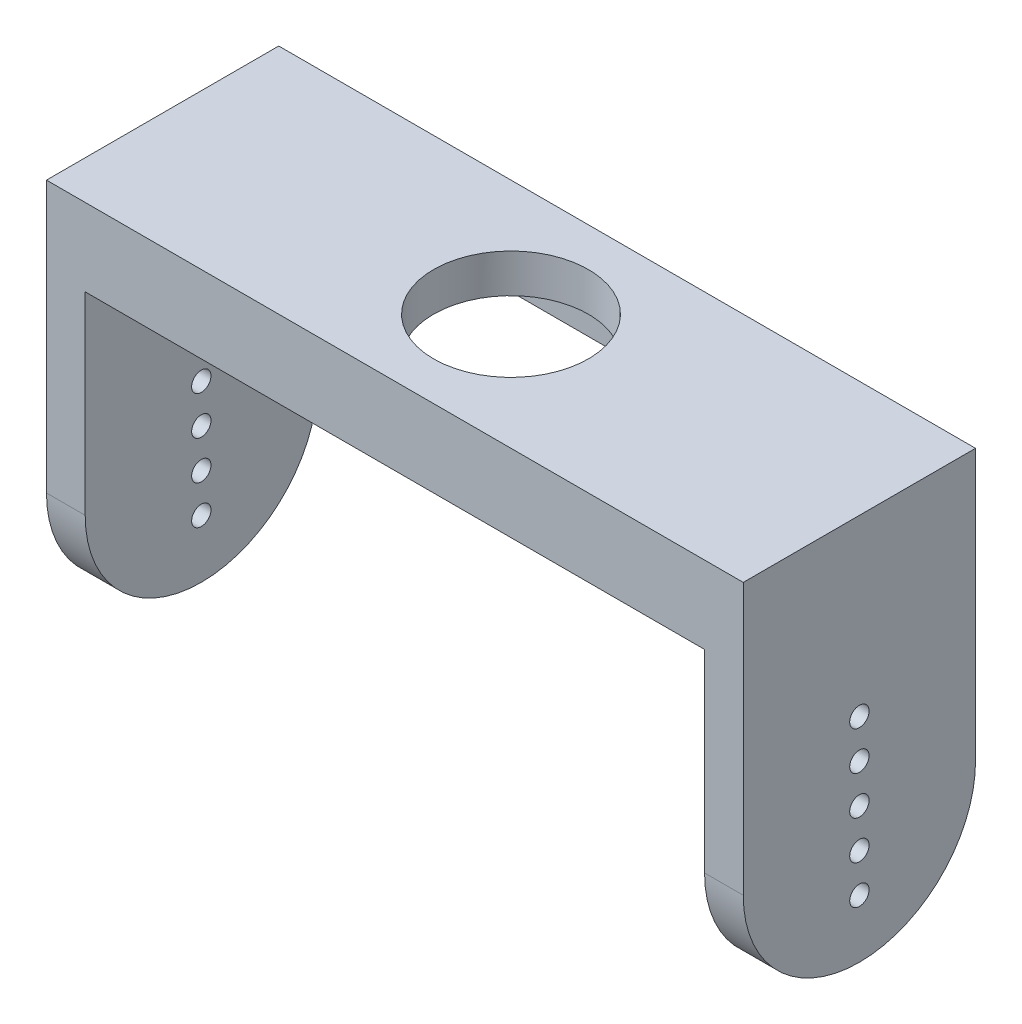
SolidWorks part; units mm, degrees
ref_plane "Front Plane" through (0, 0, 0) normal (0, 0, 1) x (1, 0, 0)
ref_plane "Top Plane" through (0, 0, 0) normal (0, 1, 0) x (1, 0, 0)
ref_plane "Right Plane" through (0, 0, 0) normal (1, 0, 0) x (0, 0, -1)
sketch "Sketch1" plane through (0, 0, 0) normal (0, 0, 1) x (1, 0, 0)
  line L1 (-18, 10) -> (18, 10)
  line L2 (-18, 10) -> (-18, -10)
  line L3 (-18, -10) -> (18, -10)
  line L4 (18, 10) -> (18, -10)
  line L5 (-18, 10) -> (18, -10) construction
  line L6 (-18, -10) -> (18, 10) construction
  point P0 (0, 0)
  dimension "D1" = 20
  dimension "D2" = 36
extrude "Boss-Extrude1" add sketch "Sketch1" along normal blind 12
sketch "Sketch2" plane through (18, 0, 0) normal (1, 0, 0) x (0, 0, -1)
  line L4 (0, -10) -> (0, 10)
  line L5 (0, 10) -> (-12, 10)
  line L6 (-12, 10) -> (-12, -10)
  line L7 (-12, -10) -> (0, -10)
  line L8 (0, -4) -> (0, 10)
  line L9 (0, 10) -> (-12, 10)
  line L10 (-12, 10) -> (-12, -4)
  arc A0 (-12, -4) -> (0, -4) centre (-6, -4) ccw
  line M1 (0, -10) -> (0, 10)
  line M3 (-12, 10) -> (-12, -10)
  line M4 (-12, -10) -> (0, -10)
  dimension "D1" = 0
sketch "Sketch3" plane through (0, 0, 12) normal (0, 0, 1) x (1, 0, 0)
  line L0 (-16, 8) -> (-16, -8)
  line L1 (-16, -8) -> (16, -8)
  line L2 (16, -8) -> (16, 8)
  line L3 (16, 8) -> (-16, 8)
  line L4 (18, -10) -> (18, 10)
  line L5 (18, 10) -> (-18, 10)
  line L6 (-18, 10) -> (-18, -10)
  line L7 (-18, -10) -> (18, -10)
  line L8 (18, -10) -> (18, 10)
  line L9 (18, 10) -> (-18, 10)
  line L10 (-18, 10) -> (-18, -10)
  line L11 (-18, -10) -> (18, -10)
  dimension "D1" = 0
  dimension "D2" = 2
extrude "Cut-Extrude1" cut sketch "Sketch3" against normal blind 12 contours L2 L3 L0 L1
sketch "Sketch4" plane through (0, -8, 0) normal (0, 1, 0) x (1, 0, 0)
  line L0 (16, 0) -> (16, -12) construction
  line L1 (-16, 0) -> (16, 0)
  line L2 (-16, 0) -> (-16, -12)
  line L3 (-16, -12) -> (16, -12)
  line L4 (16, 0) -> (16, -12)
extrude "Cut-Extrude2" cut sketch "Sketch4" against normal blind 12
extrude "Cut-Extrude3" cut sketch "Sketch2" against normal through all contours A0 M3 M4 | A0 M4 M1
sketch "Sketch5" plane through (0, 10, 0) normal (0, 1, 0) x (1, 0, 0)
  line L0 (18, -6) -> (-18, -6) construction
  line L1 (18, -12) -> (18, 0) construction
  line L2 (-18, -12) -> (-18, 0) construction
  circle A0 centre (0, -6) radius 4
  dimension "D1" = 8
extrude "Cut-Extrude4" cut sketch "Sketch5" against normal blind 10 contours A0
sketch "Sketch6" plane through (18, 0, 0) normal (1, 0, 0) x (0, 0, -1)
  circle A0 centre (-6, -7) radius 0.5
  arc A1 (-12, -4) -> (0, -4) centre (-6, -4) ccw construction
  circle A2 centre (-6, -5) radius 0.5
  circle A3 centre (-6, -3) radius 0.5
  circle A4 centre (-6, -1) radius 0.5
  circle A5 centre (-6, 1) radius 0.5
  point P5 (-6, -10)
  dimension "D1" = 3
  dimension "D2" = 5
extrude "Cut-Extrude5" cut sketch "Sketch6" against normal through all
sketch "Sketch7" plane through (0, 8, 0) normal (0, -1, 0) x (1, 0, 0)
  line L0 (16, 0) -> (16, 12) construction
  line L1 (-16, 12) -> (16, 12)
  line L2 (-16, 12) -> (-16, 11)
  line L3 (-16, 11) -> (16, 11)
  line L4 (16, 12) -> (16, 11)
  line L5 (-16, 0) -> (-16, 12) construction
  line L6 (-16, 1) -> (16, 1)
  line L7 (-16, 1) -> (-16, 0)
  line L8 (-16, 0) -> (16, 0)
  line L9 (16, 1) -> (16, 0)
  dimension "D1" = 1
  dimension "D2" = 1
extrude "Boss-Extrude2" add sketch "Sketch7" along normal blind 2
